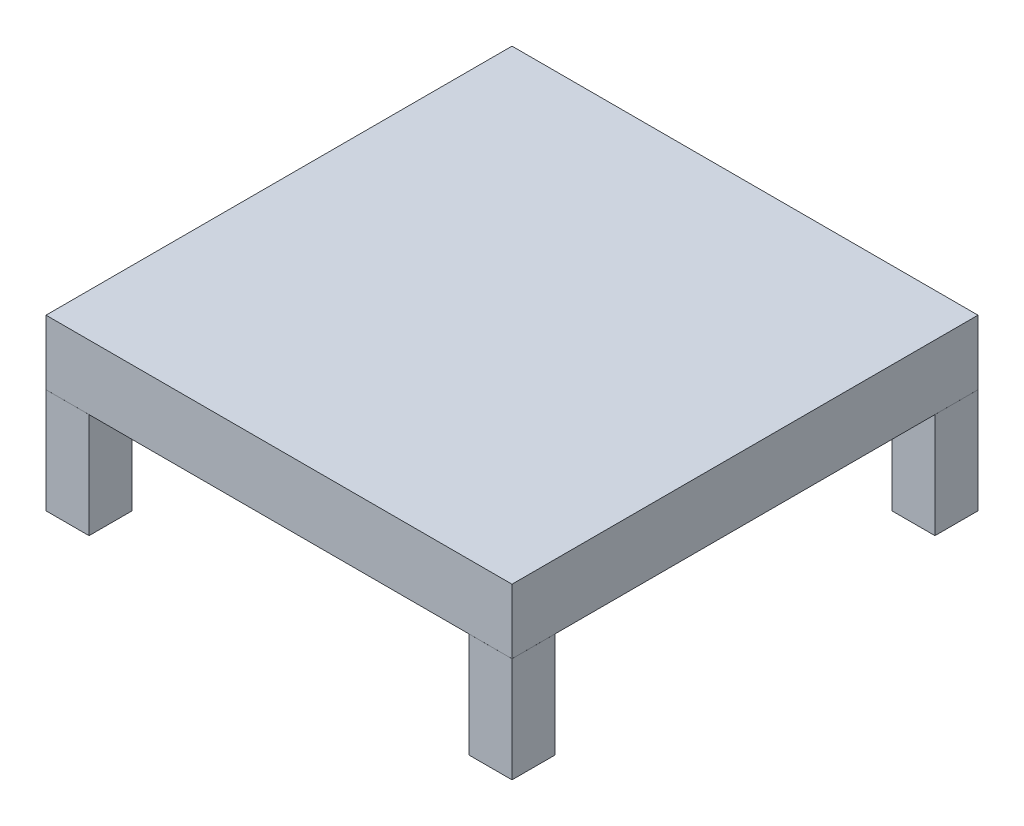
SolidWorks part; units mm, degrees
ref_plane "Front Plane" through (0, 0, 0) normal (0, 0, 1) x (1, 0, 0)
ref_plane "Top Plane" through (0, 0, 0) normal (0, 1, 0) x (1, 0, 0)
ref_plane "Right Plane" through (0, 0, 0) normal (1, 0, 0) x (0, 0, -1)
sketch "Sketch3" plane through (0, 0, 0) normal (0, 1, 0) x (1, 0, 0)
  line L0 (-275, 275) -> (275, -275) construction
  line L1 (-275, 275) -> (275, 275)
  line L2 (-275, 275) -> (-275, -275)
  line L3 (-275, -275) -> (275, -275)
  line L4 (275, 275) -> (275, -275)
  dimension "D1" = 550
extrude "Boss-Extrude2" add sketch "Sketch3" along normal mid plane 76.2
sketch "Sketch5" plane through (0, -38.1, 0) normal (0, -1, 0) x (1, 0, 0)
  line L0 (275, 0) -> (0, 0) construction
  line L1 (275, 275) -> (224.2, 275)
  line L2 (275, 275) -> (275, 224.2)
  line L3 (275, 224.2) -> (224.2, 224.2)
  line L4 (224.2, 275) -> (224.2, 224.2)
  line L5 (275, 275) -> (275, -275) construction
  line L6 (0, 0) -> (0, 275) construction
  line L7 (-275, 275) -> (275, 275) construction
  line L8 (224.2, -275) -> (224.2, -224.2)
  line L9 (275, -224.2) -> (224.2, -224.2)
  line L10 (275, -275) -> (275, -224.2)
  line L11 (275, -275) -> (224.2, -275)
  line L12 (-275, -275) -> (-224.2, -275)
  line L13 (-275, -275) -> (-275, -224.2)
  line L14 (-275, -224.2) -> (-224.2, -224.2)
  line L15 (-224.2, -275) -> (-224.2, -224.2)
  line L16 (-224.2, 275) -> (-224.2, 224.2)
  line L17 (-275, 224.2) -> (-224.2, 224.2)
  line L18 (-275, 275) -> (-275, 224.2)
  line L19 (-275, 275) -> (-224.2, 275)
  dimension "D1" = 50.8
extrude "Boss-Extrude3" add sketch "Sketch5" along normal offset from surface (373.8 mm away) 450 up to face at (0, 38.1, 0)
sketch "Sketch6" plane through (275, 0, 0) normal (1, 0, 0) x (0, 0, -1)
  line L1 (-295.1485, -38.1) -> (360.4823, -38.1)
  line L2 (-295.1485, -38.1) -> (-295.1485, -38.1254)
  line L3 (-295.1485, -38.1254) -> (360.4823, -38.1254)
  line L4 (360.4823, -38.1) -> (360.4823, -38.1254)
  dimension "D1" = 0.0254
extrude "Cut-Extrude1" cut sketch "Sketch6" against normal through all both and the other way through all
sketch "Sketch7" plane through (0, -411.9, 0) normal (0, -1, 0) x (1, 0, 0)
  line L1 (275, -275) -> (-275, -275)
  line L2 (275, -275) -> (275, 275)
  line L3 (275, 275) -> (-275, 275)
  line L4 (-275, -275) -> (-275, 275)
extrude "Cut-Extrude2" cut sketch "Sketch7" against normal offset from surface (249.975 mm away) 123.825 up to face at (0, -38.1, 0)
sketch "Sketch8" plane through (0, -38.1, 0) normal (0, -1, 0) x (1, 0, 0)
  circle A0 centre (161.147, 142.9229) radius 2.25 construction
  circle A1 centre (75.2717, -43.7903) radius 2.25 construction
  circle A2 centre (161.147, 142.9229) radius 1.996
  circle A3 centre (75.2717, -43.7903) radius 1.996
  point P4 (163.2405, 142.0983)
  point P5 (162.0979, 144.9621)
  point P6 (159.5354, 141.3529)
  point P7 (76.9827, -45.2516)
  point P10 (74.0136, -45.6557)
  point P19 (73.7808, -42.1052)
  dimension "D1" = 0.254
  dimension "D2" = 0.254
extrude "Cut-Extrude3" cut sketch "Sketch8" against normal blind 2.4765
sketch "Sketch9" plane through (0, -38.1, 0) normal (0, -1, 0) x (1, 0, 0)
  line L0 (161.147, 275) -> (161.147, 142.9229)
  line L1 (275, 142.9229) -> (161.147, 142.9229)
  line L2 (275, -43.7903) -> (75.2717, -43.7903)
  line L3 (75.2717, 275) -> (75.2717, -43.7903)
  line L4 (-275, 275) -> (275, 275) construction
  line L5 (275, 275) -> (275, -275) construction
  circle A0 centre (75.2717, -43.7903) radius 1.996 construction
  circle A1 centre (161.147, 142.9229) radius 1.996 construction
  point P1 (150.881, 140.5764)
  point P7 (186.4964, 136.7774)
  point P8 (129.0368, -18.031)
  point P9 (70.6275, -42.7244)
  point P12 (0, 0)
  point P15 (75.2717, 275)
  point P18 (161.147, 275)
  point P19 (275, -43.7903)
  point P22 (275, 142.9229)
  dimension "D1" = 318.7903
  dimension "D2" = 132.0771
  dimension "D3" = 113.853
  dimension "D4" = 199.7283
